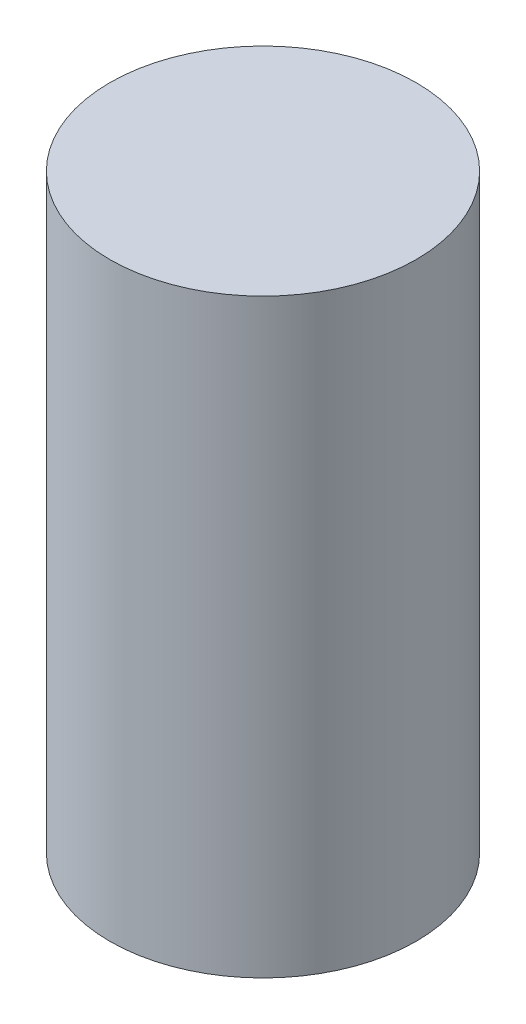
SolidWorks part; units mm, degrees
ref_plane "Front Plane" through (0, 0, 0) normal (0, 0, 1) x (1, 0, 0)
ref_plane "Top Plane" through (0, 0, 0) normal (0, 1, 0) x (1, 0, 0)
ref_plane "Right Plane" through (0, 0, 0) normal (1, 0, 0) x (0, 0, -1)
sketch "Sketch1" plane through (0, 0, 0) normal (0, 1, 0) x (1, 0, 0)
  circle A0 centre (0, 0) radius 27.5
  dimension "D1" = 55
extrude "Boss-Extrude1" add sketch "Sketch1" along normal blind 106
